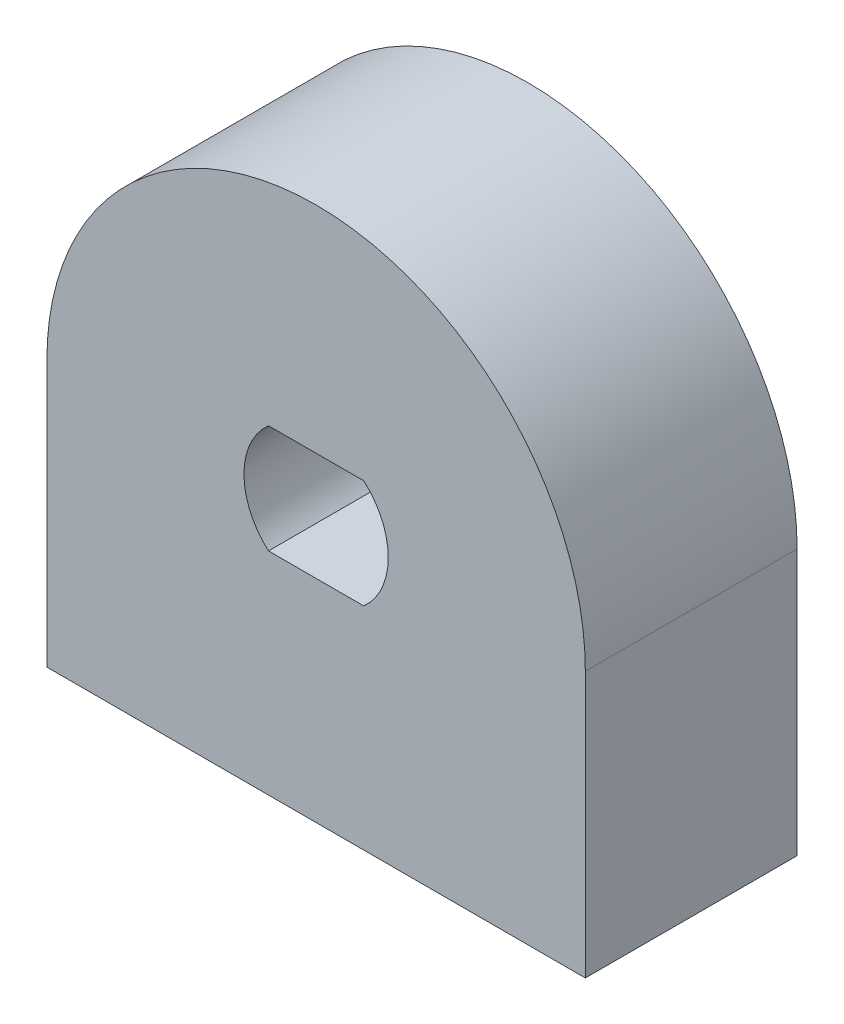
SolidWorks part; units mm, degrees
ref_plane "Plan de face" through (0, 0, 0) normal (0, 0, 1) x (1, 0, 0)
ref_plane "Plan de dessus" through (0, 0, 0) normal (0, 1, 0) x (1, 0, 0)
ref_plane "Plan de droite" through (0, 0, 0) normal (1, 0, 0) x (0, 0, -1)
sketch "Esquisse1" plane through (0, 0, 0) normal (0, 0, 1) x (1, 0, 0)
  line L0 (0, 7.4) -> (15, 7.4) construction
  line L1 (0, 0) -> (15, 0)
  line L2 (0, 0) -> (0, 7.4)
  line L3 (24.7808, 14.9) -> (-32.9953, 14.9) construction
  line L4 (15, 0) -> (15, 7.4)
  line L5 (6.1734, 8.91) -> (8.8266, 8.91)
  line L6 (6.1734, 5.89) -> (8.8266, 5.89)
  line L7 (6.1734, 8.91) -> (8.8266, 5.89) construction
  line L8 (6.1734, 5.89) -> (8.8266, 8.91) construction
  arc A0 (0, 7.4) -> (15, 7.4) centre (7.5, 7.4) cw
  arc A2 (6.1734, 8.91) -> (6.1734, 5.89) centre (7.5, 7.4) ccw
  arc A4 (8.8266, 5.89) -> (8.8266, 8.91) centre (7.5, 7.4) ccw
  point P8 (11.9943, 6.3411)
  point P13 (7.5, 7.4)
  dimension "D3" = 2.01
  dimension "D1" = 15
  dimension "D2" = 14.9
  dimension "D4" = 3.02
extrude "Extrusion1" add sketch "Esquisse1" along normal blind 5.9
